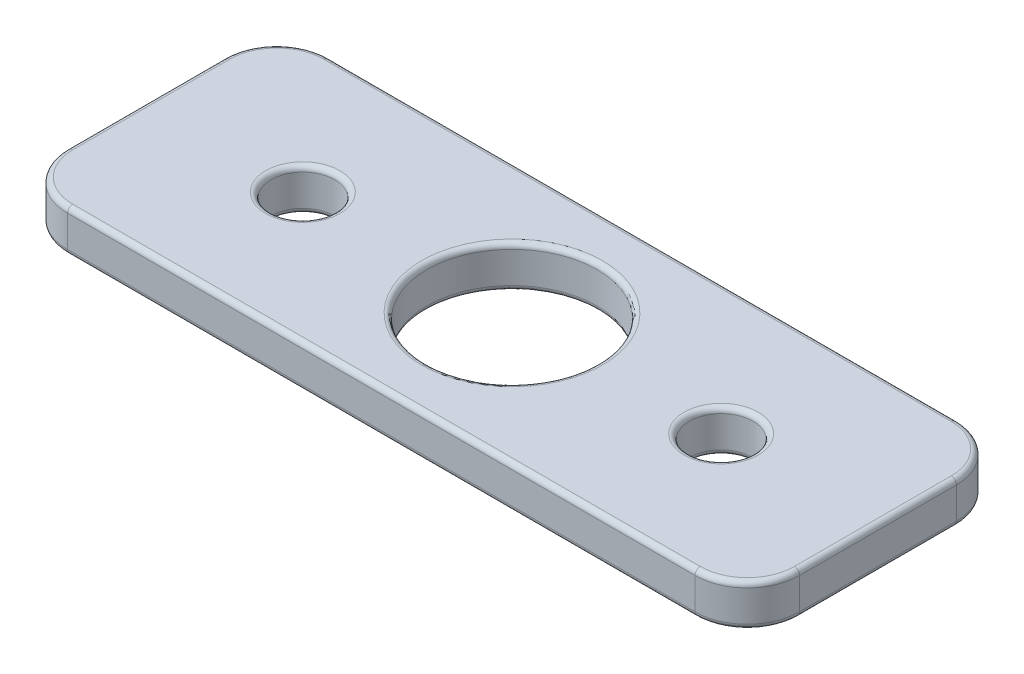
SolidWorks part; units mm, degrees
ref_plane "Front Plane" through (0, 0, 0) normal (0, 0, 1) x (1, 0, 0)
ref_plane "Top Plane" through (0, 0, 0) normal (0, 1, 0) x (1, 0, 0)
ref_plane "Right Plane" through (0, 0, 0) normal (1, 0, 0) x (0, 0, -1)
sketch "Sketch1" plane through (0, 0, 0) normal (0, 1, 0) x (1, 0, 0)
  line L0 (70, 25) -> (0, 0) construction
  line L1 (0, 0) -> (70, 0)
  line L2 (0, 0) -> (0, 25)
  line L3 (0, 25) -> (70, 25)
  line L4 (70, 0) -> (70, 25)
  line L5 (35, 12.5) -> (15, 12.5) construction
  line L6 (35, 12.5) -> (35, 25) construction
  circle A0 centre (15, 12.5) radius 3.05
  circle A1 centre (35, 12.5) radius 8.15
  circle A2 centre (55, 12.5) radius 3.05
  dimension "D3" = 6.1
  dimension "D5" = 16.3
  dimension "D1" = 70
  dimension "D2" = 25
  dimension "D4" = 20
extrude "Boss-Extrude1" add sketch "Sketch1" along normal blind 4
fillet "Fillet1" radius 5 4 edges at (70, 2, -25) (0, 2, -25) (0, 2, 0) (70, 2, 0)
fillet "Fillet2" radius 0.5 22 edges at (55, 0, -15.55) (15, 0, -9.45) (1.4645, 0, -23.5355) (0, 0, -12.5) (1.4645, 0, -1.4645) (35, 0, 0) (68.5355, 0, -1.4645) (70, 0, -12.5) (68.5355, 0, -23.5355) (35, 0, -25) (35, 0, -4.35) (55, 4, -15.55) (35, 4, -4.35) (15, 4, -9.45) (68.5355, 4, -1.4645) (35, 4, 0) (1.4645, 4, -1.4645) (0, 4, -12.5) (1.4645, 4, -23.5355) (35, 4, -25) (68.5355, 4, -23.5355) (70, 4, -12.5)
equation "\"centerDist\"=20.4228"
equation "\"sideWidth\"=25"
equation "\"D2@Sketch1\"=\"sideWidth\""
